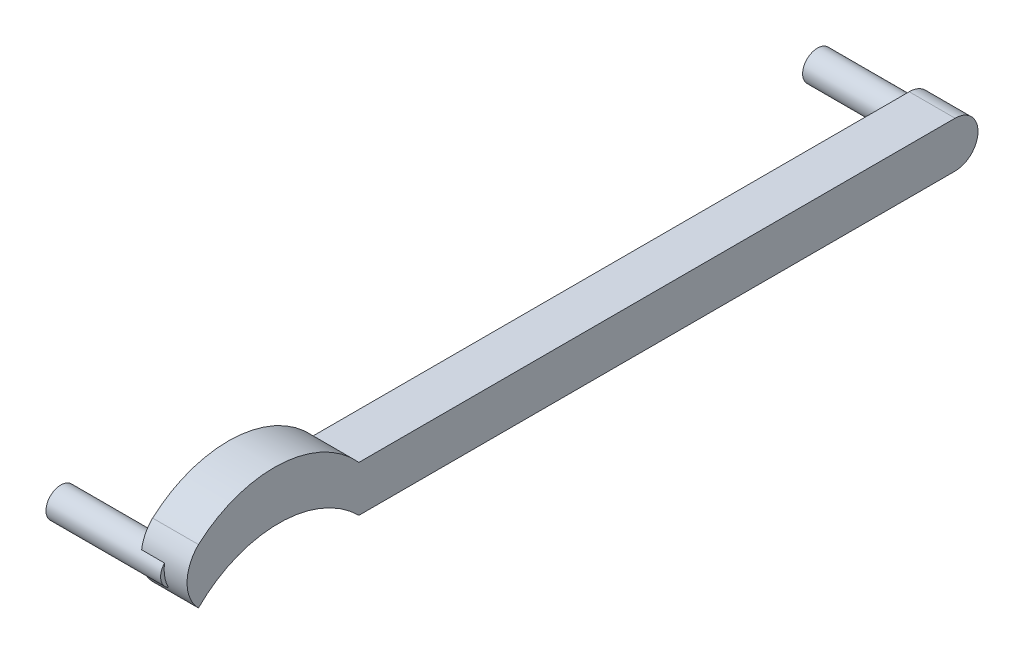
SolidWorks part; units mm, degrees
ref_plane "Front Plane" through (0, 0, 0) normal (0, 0, 1) x (1, 0, 0)
ref_plane "Top Plane" through (0, 0, 0) normal (0, 1, 0) x (1, 0, 0)
ref_plane "Right Plane" through (0, 0, 0) normal (1, 0, 0) x (0, 0, -1)
sketch "Sketch1" plane through (0, 0, 0) normal (1, 0, 0) x (0, 0, -1)
  line L0 (-16.5, 0) -> (16.5, 0) construction
  line L1 (18.9731, 0) -> (-18.9731, 0) construction
  line L2 (16.5, 1) -> (-9.5, 1)
  line L3 (0, 2.0111) -> (0, -2.0111) construction
  line L6 (16.5, -1) -> (-9.5, -1)
  line L7 (-9.5, 1) -> (-9.5, -1) construction
  arc A1 (16.5, -1) -> (16.5, 1) centre (16.5, 0) ccw
  arc A2 (-9.5, 1) -> (-16.5, 1.3976) centre (-13.1988, -2.3012) ccw
  arc A3 (-9.5, -1) -> (-16.5, -1) centre (-13, -4.5) ccw
  arc A4 (-16.5, 1.3976) -> (-16.5, -1) centre (-15.3012, 0.1988) ccw
  dimension "D1" = 33
  dimension "D2" = 16.5
  dimension "D3" = 26
sketch "Sketch2" plane through (0, 0, 0) normal (1, 0, 0) x (0, 0, -1)
  circle A0 centre (-16.5, 0) radius 0.65
  dimension "D1" = 1.3
sketch "Sketch3" plane through (0, 0, 0) normal (1, 0, 0) x (0, 0, -1)
  circle A0 centre (16.5, 0) radius 0.65
  dimension "D1" = 1.3
extrude "Boss-Extrude1" add sketch "Sketch1" along normal mid plane 2
extrude "Boss-Extrude2" add sketch "Sketch2" against normal blind 5
extrude "Boss-Extrude3" add sketch "Sketch3" against normal blind 5
